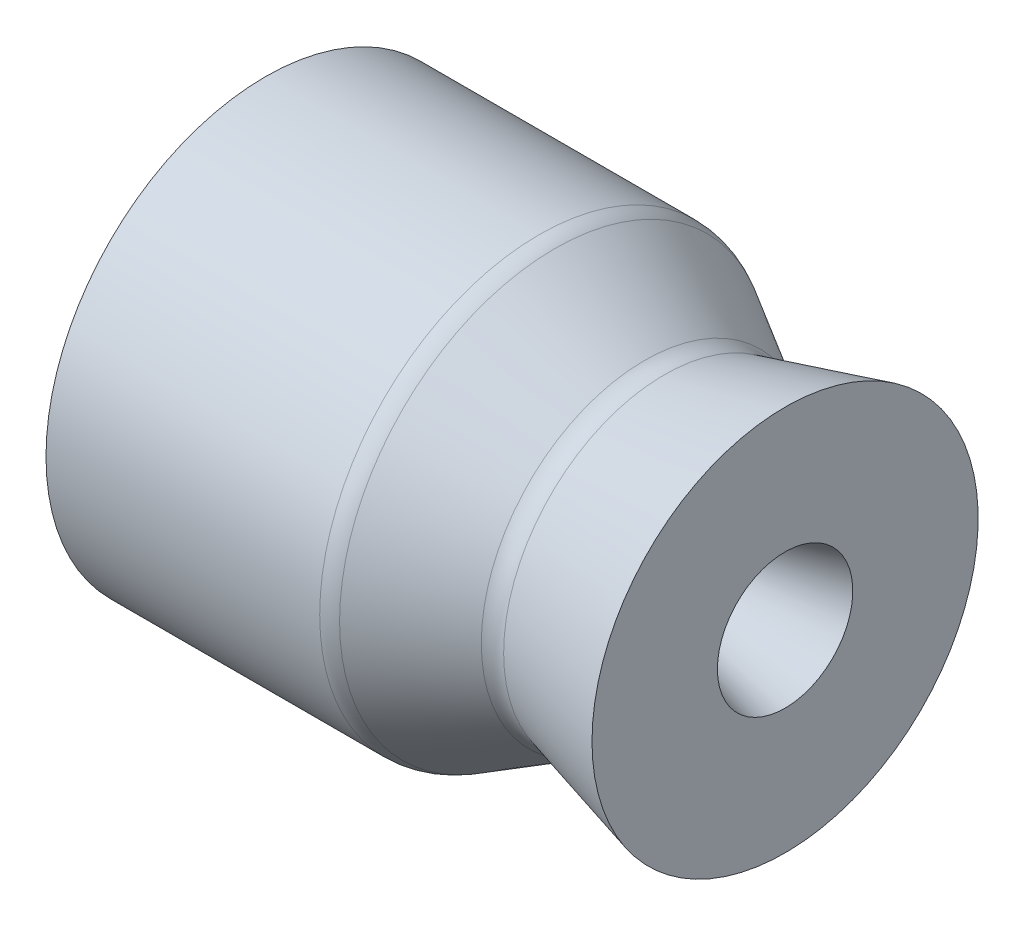
SolidWorks part; units mm, degrees
material "AISI 304"
ref_plane "Front Plane" through (0, 0, 0) normal (0, 0, 1) x (1, 0, 0)
ref_plane "Top Plane" through (0, 0, 0) normal (0, 1, 0) x (1, 0, 0)
ref_plane "Right Plane" through (0, 0, 0) normal (1, 0, 0) x (0, 0, -1)
sketch "chamberNozzle" plane through (0, 0, 0) normal (0, 0, 1) x (1, 0, 0)
  line L0 (0, 0) -> (366.3783, 0) construction
  line L1 (0, 0) -> (0, 38.1) construction
  line L2 (0, 38.1) -> (110.897, 38.1)
  line L3 (158.9188, 24.511) -> (158.9188, 13.97) construction
  line L4 (117.247, 36.3985) -> (153.6483, 15.3822)
  line L5 (150.9294, 13.97) -> (106.9103, 13.97) construction
  line L6 (161.647, 14.3292) -> (210.5452, 27.4314)
  line L7 (210.5452, 27.4314) -> (210.5452, 0) construction
  line L8 (0, 88.9) -> (110.897, 88.9)
  line L9 (117.247, 87.1985) -> (153.6483, 66.1822)
  line L10 (161.647, 65.1292) -> (210.5452, 78.2314)
  line L11 (0, 38.1) -> (0, 45.72)
  line L12 (0, 45.72) -> (5.08, 45.72)
  line L13 (5.08, 45.72) -> (5.08, 55.88)
  line L14 (5.08, 55.88) -> (0, 55.88)
  line L15 (0, 55.88) -> (0, 88.9)
  line L17 (210.5452, 78.2314) -> (210.5452, 27.4314)
  arc A0 (153.6483, 15.3822) -> (161.647, 14.3292) centre (158.9188, 24.511) ccw
  arc A1 (110.897, 38.1) -> (117.247, 36.3985) centre (110.897, 25.4) cw
  arc A2 (153.6483, 66.1822) -> (161.647, 65.1292) centre (158.9188, 75.311) ccw
  arc A3 (110.897, 88.9) -> (117.247, 87.1985) centre (110.897, 76.2) cw
  point P16 (114.3, 38.1)
  point P28 (5.08, 50.8)
  dimension "D4" = 21.082
  dimension "D9" = 12.7
  dimension "D1" = 38.1
  dimension "D3" = 13.97
  dimension "D5" = 30
  dimension "D6" = 15
  dimension "D10" = 50.8
  dimension "D11" = 10.16
  dimension "D12" = 5.08
  dimension "D13" = 12.7
revolve "Revolve1" add sketch "chamberNozzle" angle 360 about L0
ref_plane "chamberInterface" through (0, 0, 0) normal (-1, 0, 0) x (0, 0, 1)
sketch "Sketch1" plane through (0, 0, 0) normal (-1, 0, 0) x (0, 0, 1)
  circle A0 centre (0, 0) radius 72.39 construction
  dimension "D1" = 144.78
hole_wizard "1/2 (0.5) Diameter Hole1" positions "Sketch2" profile "Sketch3" hole size "1/2" standard "ANSI Inch"
sketch "Sketch2" plane through (0, 0, 0) normal (-1, 0, 0) x (0, 0, 1)
  circle A0 centre (0, 0) radius 72.39 construction
  point P0 (-72.39, 0)
sketch "Sketch3" plane through (0, 0, -72.39) normal (0, 1, 0) x (0, 0, 1)
  line L0 (0, 0) -> (0, 16.5155)
  line L1 (0, 16.5155) -> (6.35, 12.7)
  line L2 (6.35, 12.7) -> (6.35, 0.635)
  line L3 (6.35, 0.635) -> (6.985, 0)
  line L5 (6.985, 0) -> (0, 0)
  line L6 (-6.35, 0.635) -> (-6.985, 0) construction
  line L10 (0, 16.5155) -> (-6.35, 12.7) construction
  line L11 (0, -6.35) -> (0, 107.95) construction
  dimension "Hole Dia." = 12.7
  dimension "Hole Depth" = 12.7
  dimension "Near C'Sink Dia." = 13.97
  dimension "Near C'Sink Angle" = 90
  dimension "Drill Angle" = 118
pattern_circular "CirPattern1" count 6 over 360 about axis through (0, 0, 0) along (1, 0, 0) of "1/2 (0.5) Diameter Hole1"
equation "\"l_star\"= .8m'characteristic length"
equation "\"R_t\"= .55in'throat radius"
equation "\"V_c\"= \"l_star\" * \"R_t\"'chamber volume"
equation "\"D_c\"= 3in'chamber diameter"
equation "\"L_c\"= \"V_c\" / ( ( pi * \"D_c\" ) / 4 )'chamber length"
equation "\"eps_x\"= 3.8557'expansion ratio"
equation "\"D_e\"= \"R_t\" * 2 * sqr ( \"eps_x\" )'exit diameter"
equation "\"arc_t\"= 1.5in * \"R_t\"'arc between convergent and divergent"
equation "\"D3@chamberNozzle\" = \"R_t\""
equation "\"D7@chamberNozzle\" = \"D_e\" / 2"
equation "\"D1@chamberNozzle\" = \"D_c\" / 2"
equation "\"D12@chamberNozzle\"=\"D11@chamberNozzle\"/2"
equation "\"D13@chamberNozzle\"=\"D10@chamberNozzle\"/4"
